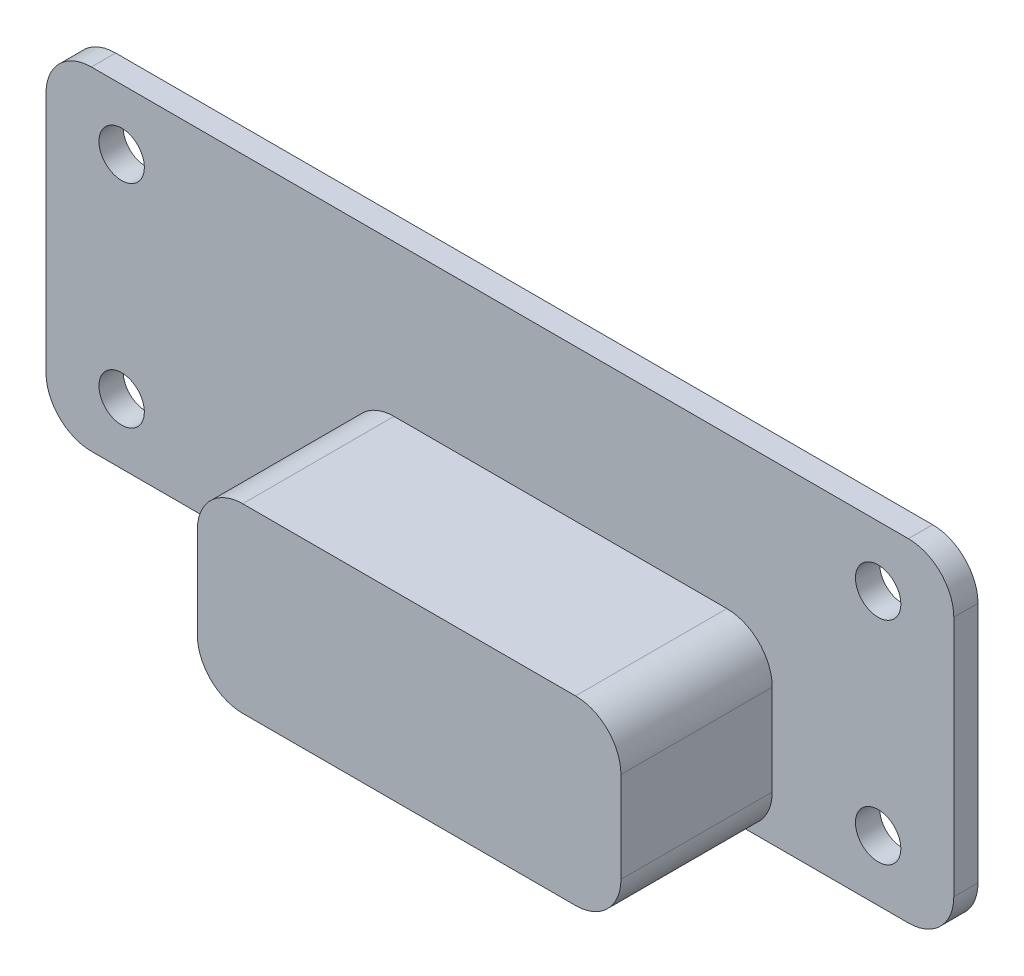
SolidWorks part; units mm, degrees
ref_plane "前视基准面" through (0, 0, 0) normal (0, 0, 1) x (1, 0, 0)
ref_plane "上视基准面" through (0, 0, 0) normal (0, 1, 0) x (1, 0, 0)
ref_plane "右视基准面" through (0, 0, 0) normal (1, 0, 0) x (0, 0, -1)
other "Configuration Table"
sketch "草图1" plane through (0, 0, 0) normal (0, 0, 1) x (1, 0, 0)
  line L0 (-38.7112, 0) -> (31.3105, 0) construction
  line L1 (0, 22.4866) -> (0, -30.1719) construction
  line L2 (-30, 8) -> (-30, -8)
  line L3 (-27, -11) -> (27, -11)
  line L4 (30, -8) -> (30, 8)
  line L5 (27, 11) -> (-27, 11)
  line L7 (-25, 7) -> (25, 7) construction
  line L8 (-25, 7) -> (-25, -7) construction
  line L9 (-25, -7) -> (25, -7) construction
  line L10 (25, 7) -> (25, -7) construction
  arc A0 (-30, -8) -> (-27, -11) centre (-27, -8) ccw
  arc A1 (27, -11) -> (30, -8) centre (27, -8) ccw
  arc A2 (30, 8) -> (27, 11) centre (27, 8) ccw
  arc A3 (-27, 11) -> (-30, 8) centre (-27, 8) ccw
  circle A4 centre (-25, 7) radius 1.5
  circle A5 centre (25, 7) radius 1.5
  circle A6 centre (25, -7) radius 1.5
  circle A7 centre (-25, -7) radius 1.5
  dimension "D5" = 3
  dimension "D8" = 3
  dimension "D1" = 22
  dimension "D2" = 60
  dimension "D3" = 50
  dimension "D4" = 14
  dimension "D6" = 7
  dimension "D7" = 25
extrude "凸台-拉伸1" add sketch "草图1" along normal blind 1.6
sketch "草图2" plane through (0, 0, 1.6) normal (0, 0, 1) x (1, 0, 0)
  line L0 (-27, -11) -> (27, -11) construction
  line L1 (-10, -11) -> (18, -11)
  line L2 (-10, -11) -> (-10, 1)
  line L3 (-10, 1) -> (18, 1)
  line L4 (18, -11) -> (18, 1)
  line L5 (30, -8) -> (30, 8) construction
  line L6 (-30, 8) -> (-30, -8) construction
  dimension "D1" = 12
  dimension "D2" = 12
  dimension "D3" = 20
extrude "凸台-拉伸2" add sketch "草图2" along normal blind 10
fillet "圆角1" radius 3 4 edges at (18, -11, 6.6) (18, 1, 6.6) (-10, -11, 6.6) (-10, 1, 6.6)
